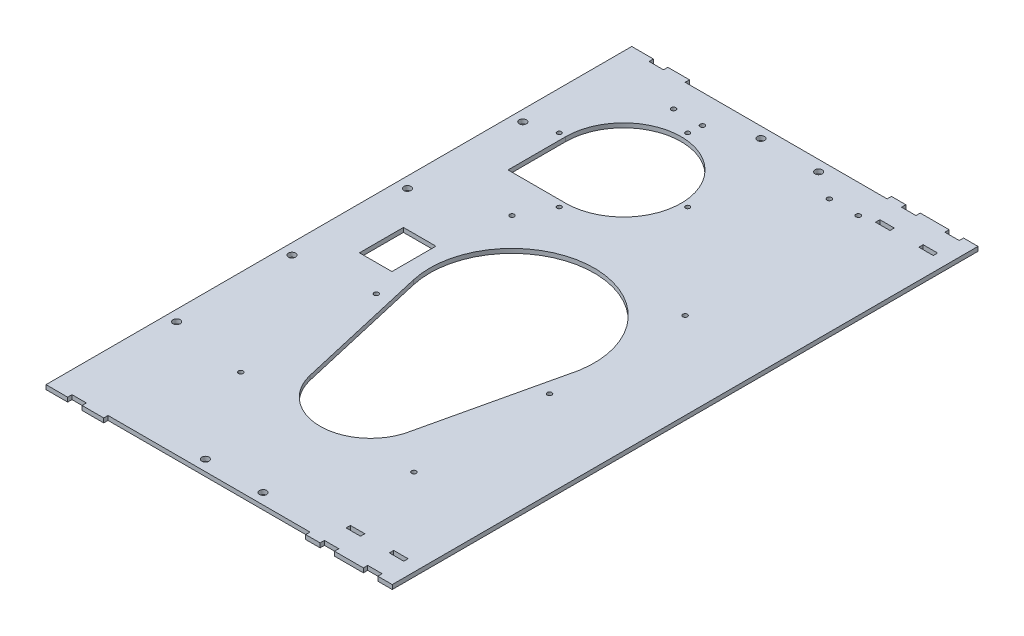
SolidWorks part; units mm, degrees
material "Thornel Mat VMA"
ref_plane "前视基准面" through (0, 0, 0) normal (0, 0, 1) x (1, 0, 0)
ref_plane "上视基准面" through (0, 0, 0) normal (0, 1, 0) x (1, 0, 0)
ref_plane "右视基准面" through (0, 0, 0) normal (1, 0, 0) x (0, 0, -1)
sketch "草图1" plane through (46.7428, 0, -86.4165) normal (0, 1, 0) x (1, 0, 0)
  line L1 (-136.7076, 113.5709) -> (103.2924, 113.5709)
  line L2 (-136.7076, 113.5709) -> (-136.7076, -286.4291)
  line L3 (-136.7076, -286.4291) -> (103.2924, -286.4291)
  line L4 (103.2924, 113.5709) -> (103.2924, -286.4291)
  line L5 (-136.7076, 113.5709) -> (103.2924, -286.4291) construction
  line L6 (-136.7076, -286.4291) -> (103.2924, 113.5709) construction
  point P0 (-16.7076, -86.4291)
  dimension "D1" = 240
  dimension "D2" = 400
extrude "凸台-拉伸1" add sketch "草图1" along normal blind 3
sketch "草图9" plane through (0, 3, 0) normal (0, 1, 0) x (1, 0, 0)
  line L0 (-89.9647, -200.0126) -> (150.0353, -200.0126) construction
  line L1 (150.0353, -200.0126) -> (140.0353, -200.0126)
  line L2 (150.0353, -200.0126) -> (150.0353, -203.0126)
  line L3 (150.0353, -203.0126) -> (140.0353, -203.0126)
  line L4 (140.0353, -200.0126) -> (140.0353, -203.0126)
  line L5 (130.0353, -200.0126) -> (110.0353, -200.0126)
  line L6 (130.0353, -200.0126) -> (130.0353, -203.0126)
  line L7 (130.0353, -203.0126) -> (110.0353, -203.0126)
  line L8 (110.0353, -200.0126) -> (110.0353, -203.0126)
  line L9 (-89.9647, -0.0126) -> (150.0353, -0.0126) construction
  line L10 (100.0353, -200.0126) -> (90.0353, -200.0126)
  line L11 (100.0353, -200.0126) -> (100.0353, -203.0126)
  line L12 (100.0353, -203.0126) -> (90.0353, -203.0126)
  line L13 (90.0353, -200.0126) -> (90.0353, -203.0126)
  line L14 (-89.9647, 199.9874) -> (-89.9647, -200.0126) construction
  line L15 (150.0353, -200.0126) -> (150.0353, 199.9874) construction
  line L16 (150.0353, 202.9874) -> (140.0353, 202.9874)
  line L17 (140.0353, 199.9874) -> (140.0353, 202.9874)
  line L18 (150.0353, 199.9874) -> (140.0353, 199.9874)
  line L19 (150.0353, 199.9874) -> (150.0353, 202.9874)
  line L20 (130.0353, 202.9874) -> (110.0353, 202.9874)
  line L21 (110.0353, 199.9874) -> (110.0353, 202.9874)
  line L22 (130.0353, 199.9874) -> (110.0353, 199.9874)
  line L23 (130.0353, 199.9874) -> (130.0353, 202.9874)
  line L24 (100.0353, 202.9874) -> (90.0353, 202.9874)
  line L25 (90.0353, 199.9874) -> (90.0353, 202.9874)
  line L26 (100.0353, 199.9874) -> (90.0353, 199.9874)
  line L27 (100.0353, 199.9874) -> (100.0353, 202.9874)
  line L28 (-64.9647, 202.9874) -> (-49.9647, 202.9874)
  line L29 (-89.9647, -200.0126) -> (-74.9647, -200.0126)
  line L30 (-89.9647, -200.0126) -> (-89.9647, -203.0126)
  line L31 (-89.9647, -203.0126) -> (-74.9647, -203.0126)
  line L32 (-74.9647, -200.0126) -> (-74.9647, -203.0126)
  line L33 (-64.9647, -200.0126) -> (-49.9647, -200.0126)
  line L34 (-64.9647, -200.0126) -> (-64.9647, -203.0126)
  line L35 (-64.9647, -203.0126) -> (-49.9647, -203.0126)
  line L36 (-49.9647, -200.0126) -> (-49.9647, -203.0126)
  line L37 (-49.9647, 199.9874) -> (-49.9647, 202.9874)
  line L38 (-64.9647, 199.9874) -> (-49.9647, 199.9874)
  line L39 (-64.9647, 199.9874) -> (-64.9647, 202.9874)
  line L40 (-89.9647, 202.9874) -> (-74.9647, 202.9874)
  line L41 (-74.9647, 199.9874) -> (-74.9647, 202.9874)
  line L42 (-89.9647, 199.9874) -> (-74.9647, 199.9874)
  line L43 (-89.9647, 199.9874) -> (-89.9647, 202.9874)
  dimension "D1" = 3
  dimension "D2" = 10
  dimension "D3" = 10
  dimension "D4" = 20
  dimension "D5" = 10
  dimension "D6" = 10
  dimension "D7" = 3
  dimension "D8" = 15
  dimension "D9" = 15
  dimension "D10" = 10
  dimension "D11" = 3
  dimension "D12" = 3
sketch "草图10" plane through (0, 3, 0) normal (0, 1, 0) x (1, 0, 0)
  line L0 (-89.9647, -200.0126) -> (150.0353, -200.0126) construction
  line L1 (150.0353, -200.0126) -> (150.0353, 199.9874) construction
  line L2 (-89.9647, 199.9874) -> (-89.9647, -200.0126) construction
  line L3 (-89.9647, 0) -> (150.0353, -0.0126) construction
  circle A1 centre (50.0353, -192.5126) radius 2.5
  circle A3 centre (10.0353, -192.5126) radius 2.5
  circle A5 centre (50.0555, 192.4979) radius 2.5
  circle A6 centre (10.0555, 192.5021) radius 2.5
  dimension "D1" = 100
  dimension "D2" = 100
  dimension "D7" = 7.5
  dimension "D8" = 7.5
sketch "草图12" plane through (0, 3, 0) normal (0, 1, 0) x (1, 0, 0)
  line L0 (-89.9647, -200.0126) -> (150.0353, -200.0126) construction
  line L1 (-89.9647, 199.9874) -> (-89.9647, -200.0126) construction
  line L2 (150.0353, 199.9874) -> (-89.9647, 199.9874) construction
  circle A0 centre (-82.4647, -120.0126) radius 2.5
  circle A1 centre (-82.4647, -40.0126) radius 2.5
  circle A2 centre (-82.4647, 119.9874) radius 2.5
  circle A3 centre (-82.4647, 39.9874) radius 2.5
  dimension "D1" = 80
  dimension "D3" = 5
  dimension "D4" = 5
  dimension "D7" = 7.5
  dimension "D9" = 5
  dimension "D10" = 5
  dimension "D2" = 80
  dimension "D5" = 7.5
  dimension "D6" = 7.5
  dimension "D8" = 7.5
  dimension "D11" = 80
  dimension "D12" = 80
sketch "草图13" plane through (0, 3, 0) normal (0, 1, 0) x (1, 0, 0)
  line L0 (-89.9647, -200.0126) -> (150.0353, -200.0126) construction
  line L1 (140.0353, -185.0126) -> (130.0353, -185.0126)
  line L2 (140.0353, -185.0126) -> (140.0353, -182.0126)
  line L3 (140.0353, -182.0126) -> (130.0353, -182.0126)
  line L4 (130.0353, -185.0126) -> (130.0353, -182.0126)
  line L5 (150.0353, -200.0126) -> (150.0353, 199.9874) construction
  line L6 (-89.9647, -200.0126) -> (150.0353, -200.0126) construction
  line L7 (110.0353, -185.0126) -> (100.0353, -185.0126)
  line L8 (110.0353, -185.0126) -> (110.0353, -182.0126)
  line L9 (110.0353, -182.0126) -> (100.0353, -182.0126)
  line L10 (100.0353, -185.0126) -> (100.0353, -182.0126)
  line L11 (-89.9647, -0.0126) -> (150.0353, -0.0126) construction
  line L12 (-89.9647, 199.9874) -> (-89.9647, -200.0126) construction
  line L13 (140.0353, 181.9874) -> (130.0353, 181.9874)
  line L14 (130.0353, 184.9874) -> (130.0353, 181.9874)
  line L15 (140.0353, 184.9874) -> (130.0353, 184.9874)
  line L16 (140.0353, 184.9874) -> (140.0353, 181.9874)
  line L17 (110.0353, 181.9874) -> (100.0353, 181.9874)
  line L18 (100.0353, 184.9874) -> (100.0353, 181.9874)
  line L19 (110.0353, 184.9874) -> (100.0353, 184.9874)
  line L20 (110.0353, 184.9874) -> (110.0353, 181.9874)
  point P18 (130.0353, -183.5126)
  dimension "D1" = 15
  dimension "D2" = 3
  dimension "D3" = 10
  dimension "D4" = 10
  dimension "D5" = 15
  dimension "D6" = 3
  dimension "D7" = 10
  dimension "D8" = 20
extrude "凸台-拉伸2" add sketch "草图9" against normal blind 3
extrude "切除-拉伸1" cut sketch "草图13" against normal blind 3
extrude "切除-拉伸2" cut sketch "草图12" against normal blind 3
extrude "切除-拉伸3" cut sketch "草图10" against normal blind 3
sketch "草图14" plane through (0, 3, 0) normal (0, 1, 0) x (1, 0, 0)
  line L0 (-89.9647, -0.0126) -> (150.0353, -0.0126) construction
  line L1 (-89.9647, 202.9874) -> (-89.9647, -203.0126) construction
  line L2 (150.0353, -203.0126) -> (150.0353, 202.9874) construction
  line L3 (30.0353, 199.9874) -> (30.0353, -200.0126) construction
  line L4 (-49.9647, -200.0126) -> (90.0353, -200.0126) construction
  line L5 (-4.0714, -105.8698) -> (-25.5099, -12.8086)
  line L6 (-3.6937, 33.7164) -> (63.7643, 33.7164) construction
  line L7 (-3.6937, 33.7164) -> (-3.6937, -33.7416) construction
  line L8 (-3.6937, -33.7416) -> (63.7643, -33.7416) construction
  line L9 (63.7643, 33.7164) -> (63.7643, -33.7416) construction
  line L10 (-3.6937, 33.7164) -> (63.7643, -33.7416) construction
  line L11 (-3.6937, -33.7416) -> (63.7643, 33.7164) construction
  line L12 (64.5046, -104.0841) -> (86.1711, -9.9004)
  line L13 (150.0353, -34.0126) -> (-89.9647, -34.0126) construction
  line L14 (90.0353, 183.3645) -> (90.0353, -251.3898) construction
  arc A0 (86.1711, -9.9004) -> (-25.5099, -12.8086) centre (30.0353, -0.0126) ccw
  arc A5 (-4.0714, -105.8698) -> (64.5046, -104.0841) centre (30.0353, -98.0126) ccw
  circle A6 centre (90.0353, -34.0126) radius 1.6
  circle A7 centre (-29.9647, -34.0126) radius 1.6
  circle A8 centre (90.0353, -128.0126) radius 1.6
  circle A9 centre (-29.9647, -128.0126) radius 1.6
  circle A10 centre (-29.9647, 59.9874) radius 1.6
  circle A11 centre (90.0353, 59.9874) radius 1.6
  point P11 (30.0353, -0.0126)
  point P30 (90.0353, -34.0126)
  dimension "D1" = 114
  dimension "D4" = 98
  dimension "D5" = 70
  dimension "D7" = 3.2
  dimension "D8" = 60
  dimension "D9" = 3.2
  dimension "D10" = 94
  dimension "D2" = 95.4
  dimension "D3" = 45
  dimension "D6" = 34
extrude "切除-拉伸4" cut sketch "草图14" against normal blind 3
sketch "草图21" plane through (0, 3, 0) normal (0, 1, 0) x (1, 0, 0)
  line L0 (150.0353, -0.0126) -> (-89.9647, -0.0126) construction
  line L1 (-89.9647, 202.9874) -> (-89.9647, -203.0126) construction
  line L2 (30.0353, 254.3079) -> (30.0353, -254.3332) construction
  line L3 (150.0353, -34.0126) -> (-89.9647, -34.0126) construction
  line L4 (150.0353, -203.0126) -> (150.0353, 202.9874) construction
  line L6 (96.0353, 65.9874) -> (-35.9647, 65.9874) construction
  line L7 (96.0353, 65.9874) -> (96.0353, -134.0126) construction
  line L8 (96.0353, -134.0126) -> (-35.9647, -134.0126) construction
  line L9 (-35.9647, 65.9874) -> (-35.9647, -134.0126) construction
  line L10 (30.0353, -134.0126) -> (30.0353, 65.9874) construction
  line L11 (96.0353, -34.0126) -> (-35.9647, -34.0126) construction
  line L12 (-60.4647, 15.2374) -> (-37.9647, 15.2374)
  line L13 (-60.4647, 15.2374) -> (-60.4647, -15.2626)
  line L14 (-60.4647, -15.2626) -> (-37.9647, -15.2626)
  line L15 (-37.9647, 15.2374) -> (-37.9647, -15.2626)
  line L16 (-49.2147, -15.2626) -> (-49.2147, 15.2374) construction
  line L17 (-60.4647, -0.0126) -> (-37.9647, -0.0126) construction
  point P3 (-49.2147, -0.0126)
  point P6 (30.0353, -0.0126)
  point P9 (30.0353, -0.0126)
  point P13 (30.0353, -34.0126)
  dimension "D1" = 132
  dimension "D2" = 200
  dimension "D3" = 34
  dimension "D4" = 22.5
  dimension "D5" = 30.5
  dimension "D6" = 2
sketch "草图23" plane through (0, 3, 0) normal (0, 1, 0) x (1, 0, 0)
  line L0 (-18.7147, 165.9874) -> (-18.7147, 85.9874) construction
  line L1 (-58.7147, 125.9874) -> (21.2853, 125.9874) construction
  line L2 (30.0353, 254.3079) -> (30.0353, -254.3332) construction
  line L3 (-18.7147, 125.9874) -> (-18.7147, 54.9263) construction
  line L4 (-18.7147, 125.9874) -> (-18.7147, 187.6522) construction
  line L5 (150.0353, -0.0126) -> (-89.9647, -0.0126) construction
  line L6 (-58.7147, 125.9874) -> (-58.7147, 85.9874)
  line L7 (-58.7147, 85.9874) -> (-18.7147, 85.9874)
  arc A0 (-18.7147, 85.9874) -> (-58.7147, 125.9874) centre (-18.7147, 125.9874) ccw
  circle A5 centre (-18.7147, 170.4874) radius 1.5
  circle A6 centre (25.7853, 125.9874) radius 1.5
  circle A7 centre (-18.7147, 81.4874) radius 1.5
  circle A8 centre (-63.2147, 125.9874) radius 1.5
  dimension "D1" = 126
  dimension "D2" = 80
  dimension "D3" = 3
  dimension "D4" = 44.5
  dimension "D5" = 48.75
  dimension "D6" = 4
extrude "切除-拉伸11" cut sketch "草图23" against normal blind 10
extrude "切除-拉伸12" cut sketch "草图21" against normal blind 10
sketch "草图24" plane through (0, 0, 0) normal (0, -1, 0) x (1, 0, 0)
  line L0 (-89.9647, -179.9874) -> (150.0353, -179.9874) construction
  line L1 (-89.9647, -202.9874) -> (-89.9647, 203.0126) construction
  line L2 (150.0353, 203.0126) -> (150.0353, -202.9874) construction
  line L3 (90.0353, -199.9874) -> (-49.9647, -199.9874) construction
  circle A0 centre (-37.9647, -179.9874) radius 1.625
  circle A1 centre (-17.9647, -179.9874) radius 1.625
  circle A2 centre (90.0353, -179.9874) radius 1.625
  circle A3 centre (70.0353, -179.9874) radius 1.625
  dimension "D1" = 3.25
  dimension "D2" = 3.25
  dimension "D3" = 20
  dimension "D5" = 52
  dimension "D6" = 3.25
  dimension "D7" = 3.25
  dimension "D8" = 20
  dimension "D9" = 80
  dimension "D4" = 20
extrude "切除-拉伸13" cut sketch "草图24" against normal blind 10
